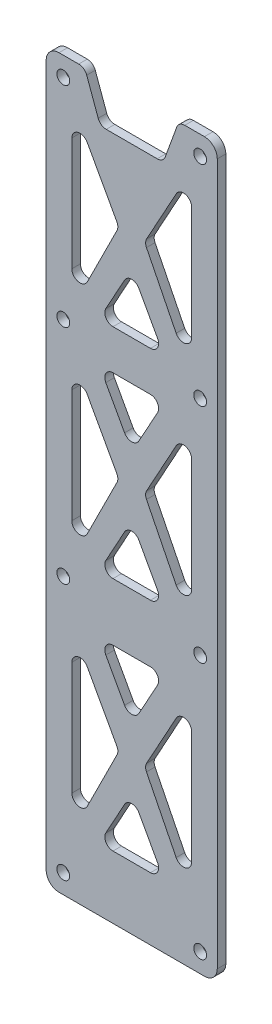
SolidWorks part; units mm, degrees
material "Thornel Mat VMA"
ref_plane "Alzado" through (0, 0, 0) normal (0, 0, 1) x (1, 0, 0)
ref_plane "Planta" through (0, 0, 0) normal (0, 1, 0) x (1, 0, 0)
ref_plane "Vista lateral" through (0, 0, 0) normal (1, 0, 0) x (0, 0, -1)
sketch "Croquis1" plane through (0, 0, 0) normal (0, 0, 1) x (1, 0, 0)
  line L1 (-17, 93.75) -> (17, 93.75)
  line L2 (-20, 90.75) -> (-20, -73.25)
  line L3 (-17, -76.25) -> (17, -76.25)
  line L4 (20, 90.75) -> (20, -73.25)
  circle A2 centre (-16, 89.25) radius 1.5
  circle A3 centre (16, 89.25) radius 1.5
  circle A4 centre (-16, 40.25) radius 1.5
  circle A5 centre (16, 40.25) radius 1.5
  circle A6 centre (-16, -11.75) radius 1.5
  circle A7 centre (16, -11.75) radius 1.5
  circle A8 centre (-16, -71.75) radius 1.5
  circle A9 centre (16, -71.75) radius 1.5
  arc A11 (-17, 93.75) -> (-20, 90.75) centre (-17, 90.75) ccw
  arc A12 (17, 93.75) -> (20, 90.75) centre (17, 90.75) cw
  arc A13 (17, -76.25) -> (20, -73.25) centre (17, -73.25) ccw
  arc A14 (-20, -73.25) -> (-17, -76.25) centre (-17, -73.25) ccw
  dimension "D2" = 3
  dimension "D3" = 49
  dimension "D4" = 52
  dimension "D5" = 4.5
  dimension "D6" = 4.5
  dimension "D7" = 4.5
  dimension "D8" = 49
  dimension "D9" = 52
  dimension "D10" = 4.5
  dimension "D11" = 32
  dimension "D12" = 32
  dimension "D13" = 40
  dimension "D14" = 60
  dimension "D15" = 32
  dimension "D16" = 4
  dimension "D17" = 4
  dimension "D18" = 4
  dimension "D19" = 4
  dimension "D20" = 60
extrude "Saliente-Extruir1" add sketch "Croquis1" along normal blind 2
sketch "Croquis2" plane through (0, 0, 2) normal (0, 0, 1) x (1, 0, 0)
  line L0 (-17, 93.75) -> (-12.4004, 93.75)
  line L1 (17, 93.75) -> (-17, 93.75) construction
  line L2 (-10.521, 92.434) -> (-7.8393, 85.066)
  line L3 (-5.9599, 83.75) -> (5.9599, 83.75)
  line L4 (7.8393, 85.066) -> (10.521, 92.434)
  line L5 (12.4004, 93.75) -> (17, 93.75)
  line L6 (-14, -28.1777) -> (-14, -54.6682)
  line L7 (-10.3857, -55.5214) -> (-3.4477, -41.6454)
  line L8 (-3.4825, -39.8728) -> (-10.4205, -27.2583)
  line L9 (0, -71.75) -> (0, -11.75) construction
  line L10 (-20, 90.75) -> (-20, -73.25) construction
  line L11 (3.4825, -39.8728) -> (10.4205, -27.2583)
  line L12 (10.3857, -55.5214) -> (3.4477, -41.6454)
  line L13 (14, -28.1777) -> (14, -54.6682)
  line L14 (-6.0573, -22.7411) -> (-1.6717, -30.7149)
  line L15 (1.6717, -30.7149) -> (6.0573, -22.7411)
  line L16 (4.3856, -19.9138) -> (-4.3856, -19.9138)
  line L17 (-3, -40.75) -> (3, -40.75) construction
  line L18 (4.3856, -61.5862) -> (-4.3856, -61.5862)
  line L19 (1.6717, -50.7851) -> (6.0573, -58.7589)
  line L20 (-6.0573, -58.7589) -> (-1.6717, -50.7851)
  line L21 (-14, 26.9861) -> (-14, 0.4956)
  line L22 (-10.3857, -0.3576) -> (-3.4477, 13.5184)
  line L23 (-3.4825, 15.291) -> (-10.4205, 27.9056)
  line L24 (3.4825, 15.291) -> (10.4205, 27.9056)
  line L25 (10.3857, -0.3576) -> (3.4477, 13.5184)
  line L26 (14, 26.9861) -> (14, 0.4956)
  line L27 (-6.0573, 32.4227) -> (-1.6717, 24.449)
  line L28 (1.6717, 24.449) -> (6.0573, 32.4227)
  line L29 (4.3856, 35.25) -> (-4.3856, 35.25)
  line L30 (4.3856, -6.4223) -> (-4.3856, -6.4223)
  line L31 (1.6717, 4.3787) -> (6.0573, -3.5951)
  line L32 (-6.0573, -3.5951) -> (-1.6717, 4.3787)
  line L33 (-14, 77.9861) -> (-14, 51.4956)
  line L34 (-3, 14.4138) -> (3, 14.4138) construction
  line L44 (-10.3857, 50.6424) -> (-3.4477, 64.5184)
  line L45 (-3.4825, 66.291) -> (-10.4205, 78.9056)
  line L46 (3.4825, 66.291) -> (10.4205, 78.9056)
  line L47 (10.3857, 50.6424) -> (3.4477, 64.5184)
  line L48 (14, 77.9861) -> (14, 51.4956)
  line L49 (4.3856, 44.5777) -> (-4.3856, 44.5777)
  line L50 (1.6717, 55.3787) -> (6.0573, 47.4049)
  line L51 (-6.0573, 47.4049) -> (-1.6717, 55.3787)
  line L52 (-3, 65.4138) -> (3, 65.4138) construction
  line L54 (0, -16.5862) -> (0, 43.4138) construction
  arc A0 (10.521, 92.434) -> (12.4004, 93.75) centre (12.4004, 91.75) cw
  arc A1 (5.9599, 83.75) -> (7.8393, 85.066) centre (5.9599, 85.75) ccw
  arc A2 (-7.8393, 85.066) -> (-5.9599, 83.75) centre (-5.9599, 85.75) ccw
  arc A3 (-12.4004, 93.75) -> (-10.521, 92.434) centre (-12.4004, 91.75) cw
  circle A4 centre (-16, -71.75) radius 1.5 construction
  circle A5 centre (-16, -11.75) radius 1.5 construction
  arc A6 (10.3857, -55.5214) -> (14, -54.6682) centre (12.0921, -54.6682) ccw
  arc A7 (10.4205, -27.2583) -> (14, -28.1777) centre (12.0921, -28.1777) cw
  arc A8 (3.4825, -39.8728) -> (3.4477, -41.6454) centre (5.1542, -40.7922) ccw
  arc A9 (-3.4477, -41.6454) -> (-3.4825, -39.8728) centre (-5.1542, -40.7922) ccw
  arc A10 (-14, -28.1777) -> (-10.4205, -27.2583) centre (-12.0921, -28.1777) cw
  arc A11 (-14, -54.6682) -> (-10.3857, -55.5214) centre (-12.0921, -54.6682) ccw
  arc A12 (6.0573, -22.7411) -> (4.3856, -19.9138) centre (4.3856, -21.8217) ccw
  arc A13 (-6.0573, -22.7411) -> (-4.3856, -19.9138) centre (-4.3856, -21.8217) cw
  arc A14 (-1.6717, -30.7149) -> (1.6717, -30.7149) centre (0, -29.7954) ccw
  arc A15 (4.3856, -61.5862) -> (6.0573, -58.7589) centre (4.3856, -59.6783) ccw
  arc A16 (1.6717, -50.7851) -> (-1.6717, -50.7851) centre (0, -51.7046) ccw
  arc A17 (-4.3856, -61.5862) -> (-6.0573, -58.7589) centre (-4.3856, -59.6783) cw
  arc A18 (10.3857, -0.3576) -> (14, 0.4956) centre (12.0921, 0.4956) ccw
  arc A19 (10.4205, 27.9056) -> (14, 26.9861) centre (12.0921, 26.9861) cw
  arc A20 (3.4825, 15.291) -> (3.4477, 13.5184) centre (5.1542, 14.3716) ccw
  arc A21 (-3.4477, 13.5184) -> (-3.4825, 15.291) centre (-5.1542, 14.3716) ccw
  arc A22 (-14, 26.9861) -> (-10.4205, 27.9056) centre (-12.0921, 26.9861) cw
  arc A23 (-14, 0.4956) -> (-10.3857, -0.3576) centre (-12.0921, 0.4956) ccw
  arc A24 (6.0573, 32.4227) -> (4.3856, 35.25) centre (4.3856, 33.3421) ccw
  arc A25 (-6.0573, 32.4227) -> (-4.3856, 35.25) centre (-4.3856, 33.3421) cw
  arc A26 (-1.6717, 24.449) -> (1.6717, 24.449) centre (0, 25.3684) ccw
  arc A27 (4.3856, -6.4223) -> (6.0573, -3.5951) centre (4.3856, -4.5145) ccw
  arc A28 (1.6717, 4.3787) -> (-1.6717, 4.3787) centre (0, 3.4593) ccw
  arc A29 (-4.3856, -6.4223) -> (-6.0573, -3.5951) centre (-4.3856, -4.5145) cw
  circle A30 centre (-16, 40.25) radius 1.5 construction
  arc A40 (10.3857, 50.6424) -> (14, 51.4956) centre (12.0921, 51.4956) ccw
  arc A41 (10.4205, 78.9056) -> (14, 77.9861) centre (12.0921, 77.9861) cw
  arc A42 (3.4825, 66.291) -> (3.4477, 64.5184) centre (5.1542, 65.3716) ccw
  arc A43 (-3.4477, 64.5184) -> (-3.4825, 66.291) centre (-5.1542, 65.3716) ccw
  arc A44 (-14, 77.9861) -> (-10.4205, 78.9056) centre (-12.0921, 77.9861) cw
  arc A45 (-14, 51.4956) -> (-10.3857, 50.6424) centre (-12.0921, 51.4956) ccw
  arc A46 (4.3856, 44.5777) -> (6.0573, 47.4049) centre (4.3856, 46.4855) ccw
  arc A47 (1.6717, 55.3787) -> (-1.6717, 55.3787) centre (0, 54.4593) ccw
  arc A48 (-4.3856, 44.5777) -> (-6.0573, 47.4049) centre (-4.3856, 46.4855) cw
  point P12 (11, 93.75)
  point P19 (-11, 93.75)
  point P43 (14, -62.75)
  point P46 (14, -20.75)
  point P55 (-14, -20.75)
  point P58 (-14, -62.75)
  point P61 (7.6123, -19.9138)
  point P64 (-7.6123, -19.9138)
  point P67 (0, -33.7543)
  point P70 (7.6123, -61.5862)
  point P73 (0, -47.7457)
  point P76 (-7.6123, -61.5862)
  line M7 (17, 93.75) -> (-17, 93.75)
  dimension "D6" = 2
  dimension "D10" = 9
  dimension "D14" = 1.9079
  dimension "D1" = 6
  dimension "D2" = 6
  dimension "D3" = 10
  dimension "D4" = 2
  dimension "D7" = 3
  dimension "D8" = 6
  dimension "D9" = 9
  dimension "D11" = 22
  dimension "D12" = 6
  dimension "D13" = 15.2245
  dimension "D16" = 5
  dimension "D15" = 2
extrude "Cortar-Extruir1" cut sketch "Croquis2" against normal blind 2 and the other way through all contours A3 L2 A2 L3 A1 L4 A0 M7 | A48 L49 A46 L50 A47 L51 | L33 A45 L44 A43 L45 A44
